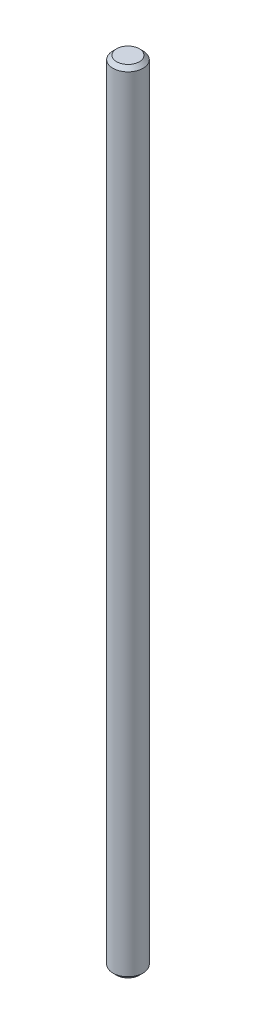
SolidWorks part; units mm, degrees
material "AISI 321 Annealed Stainless Steel (SS)"
ref_plane "Front Plane" through (0, 0, 0) normal (0, 0, 1) x (1, 0, 0)
ref_plane "Top Plane" through (0, 0, 0) normal (0, 1, 0) x (1, 0, 0)
ref_plane "Right Plane" through (0, 0, 0) normal (1, 0, 0) x (0, 0, -1)
sketch "Sketch1" plane through (0, 0, 0) normal (0, 1, 0) x (1, 0, 0)
  circle A0 centre (0, 0) radius 2
  dimension "D1" = 4
extrude "Boss-Extrude1" add sketch "Sketch1" along normal mid plane 105
chamfer "Chamfer1" distance 0.5 angle 45 2 edges at (0, 52.5, 2) (0, -52.5, 2)
cosmetic thread "Cosmetic Thread1" parameters "D1"=8, "D2"=3.22
cosmetic thread "Cosmetic Thread2" parameters "D1"=16, "D2"=3.22
